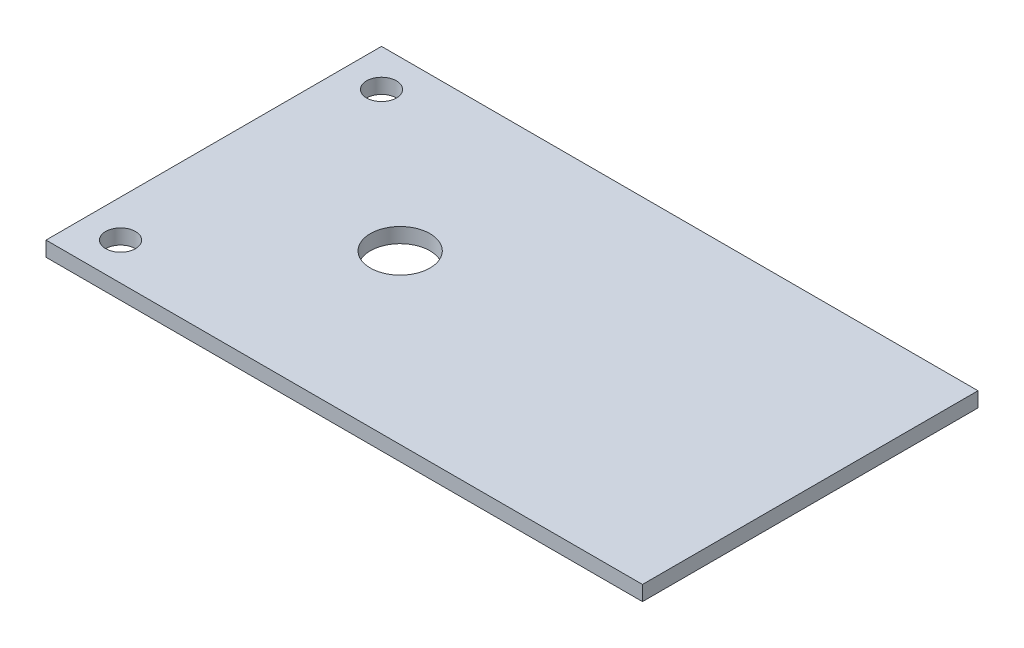
SolidWorks part; units mm, degrees
ref_plane "前视" through (0, 0, 0) normal (0, 0, 1) x (1, 0, 0)
ref_plane "上视" through (0, 0, 0) normal (0, 1, 0) x (1, 0, 0)
ref_plane "右视" through (0, 0, 0) normal (1, 0, 0) x (0, 0, -1)
sketch "Sketch1" plane through (0, 0, 0) normal (0, 1, 0) x (1, 0, 0)
  line L1 (0, 0) -> (160, 0)
  line L2 (0, 0) -> (0, 90)
  line L3 (0, 90) -> (160, 90)
  line L4 (160, 0) -> (160, 90)
  circle A0 centre (10, 10) radius 4
  circle A1 centre (10, 80) radius 4
  circle A2 centre (50, 45) radius 8
  dimension "D3" = 10
  dimension "D5" = 10
  dimension "D6" = 50
  dimension "D1" = 160
  dimension "D2" = 90
  dimension "D4" = 10
extrude "Extrude1" add sketch "Sketch1" along normal blind 4
